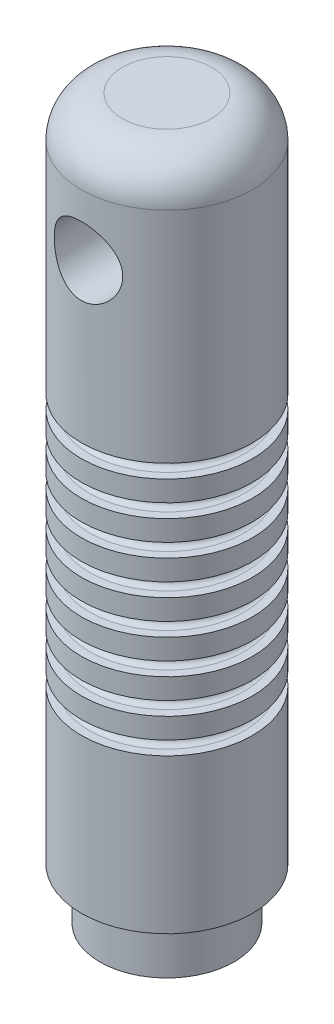
SolidWorks part; units mm, degrees
ref_plane "Front Plane" through (0, 0, 0) normal (0, 0, 1) x (1, 0, 0)
ref_plane "Top Plane" through (0, 0, 0) normal (0, 1, 0) x (1, 0, 0)
ref_plane "Right Plane" through (0, 0, 0) normal (1, 0, 0) x (0, 0, -1)
sketch "Sketch1" plane through (0, 0, 0) normal (0, 0, 1) x (1, 0, 0)
  line L0 (0, 80.3516) -> (0, -75.462) construction
  line L1 (0, 0) -> (12.446, 0)
  line L2 (12.446, 0) -> (12.446, 9.525)
  line L3 (12.446, 9.525) -> (15.875, 9.525)
  line L4 (15.875, 9.525) -> (15.875, 125.73)
  line L5 (0, 133.35) -> (8.255, 133.35)
  line L6 (0, 133.35) -> (0, 0)
  arc A0 (15.875, 125.73) -> (8.255, 133.35) centre (8.255, 125.73) ccw
  point P11 (15.875, 133.35)
  dimension "D5" = 7.62
  dimension "D1" = 133.35
  dimension "D2" = 15.875
  dimension "D3" = 9.525
  dimension "D4" = 12.446
revolve "Revolve1" add sketch "Sketch1" angle 360 about L0
sketch "Sketch2" plane through (0, 0, 0) normal (0, 0, 1) x (1, 0, 0)
  line L0 (0, 121.2288) -> (0, -1.9421) construction
  line L1 (15.875, 40.64) -> (14.351, 40.64)
  line L2 (15.875, 9.525) -> (15.875, 125.73) construction
  line L3 (13.335, 39.624) -> (13.335, 39.116)
  line L4 (14.351, 38.1) -> (15.875, 38.1)
  line L5 (15.875, 38.1) -> (15.875, 40.64)
  line L6 (-12.446, 0) -> (12.446, 0) construction
  arc A0 (14.351, 38.1) -> (13.335, 39.116) centre (14.351, 39.116) cw
  arc A1 (13.335, 39.624) -> (14.351, 40.64) centre (14.351, 39.624) cw
  point P15 (13.335, 40.64)
  dimension "D4" = 1.016
  dimension "D1" = 2.54
  dimension "D2" = 2.54
  dimension "D3" = 38.1
revolve "Cut-Revolve1" cut sketch "Sketch2" angle 360 about L0
pattern_linear "LPattern1" count 8 spacing 6.35 along (0, 1, 0) of "Cut-Revolve1"
sketch "Sketch3" plane through (0, 0, 0) normal (0, -1, 0) x (1, 0, 0)
  line L1 (-6.35, 1.2192) -> (6.35, 1.2192)
  line L2 (-6.35, 1.2192) -> (-6.35, -1.2192)
  line L3 (-6.35, -1.2192) -> (6.35, -1.2192)
  line L4 (6.35, 1.2192) -> (6.35, -1.2192)
  line L5 (-6.35, 1.2192) -> (6.35, -1.2192) construction
  line L6 (-6.35, -1.2192) -> (6.35, 1.2192) construction
  point P0 (0, 0)
  dimension "D1" = 12.7
  dimension "D2" = 2.4384
extrude "Cut-Extrude1" cut sketch "Sketch3" against normal blind 19.05
sketch "Sketch4" plane through (0, 0, 0) normal (0, 0, 1) x (1, 0, 0)
  line L0 (0, 138.9904) -> (0, 0) construction
  line L1 (-12.446, 0) -> (12.446, 0) construction
  circle A0 centre (0, 114.3) radius 6.35
  dimension "D1" = 12.7
  dimension "D2" = 114.3
extrude "Cut-Extrude3" cut sketch "Sketch4" against normal through all both and the other way through all
